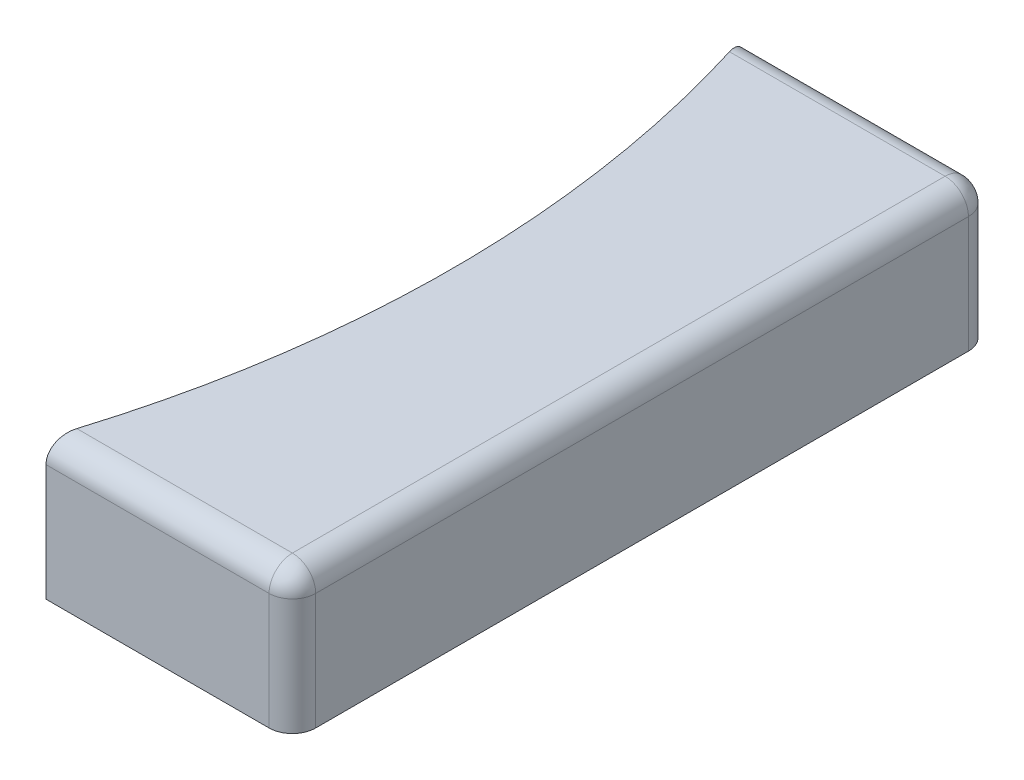
SolidWorks part; units mm, degrees
ref_plane "Front Plane" through (0, 0, 0) normal (0, 0, 1) x (1, 0, 0)
ref_plane "Top Plane" through (0, 0, 0) normal (0, 1, 0) x (1, 0, 0)
ref_plane "Right Plane" through (0, 0, 0) normal (1, 0, 0) x (0, 0, -1)
sketch "Sketch1" plane through (0, 0, 0) normal (0, 1, 0) x (1, 0, 0)
  line L0 (0, 0) -> (10.57, 0)
  line L1 (10.57, 0) -> (10.57, -30)
  line L2 (10.57, -30) -> (0, -30)
  arc A0 (0, -30) -> (0, 0) centre (-45, -15) ccw
extrude "Boss-Extrude1" add sketch "Sketch1" along normal blind 6
shell "Shell1" thickness 1
fillet "Fillet1" radius 1 5 edges at (5.285, 6, 0) (5.285, 6, 30) (10.57, 3, 0) (10.57, 3, 30) (10.57, 6, 15)
